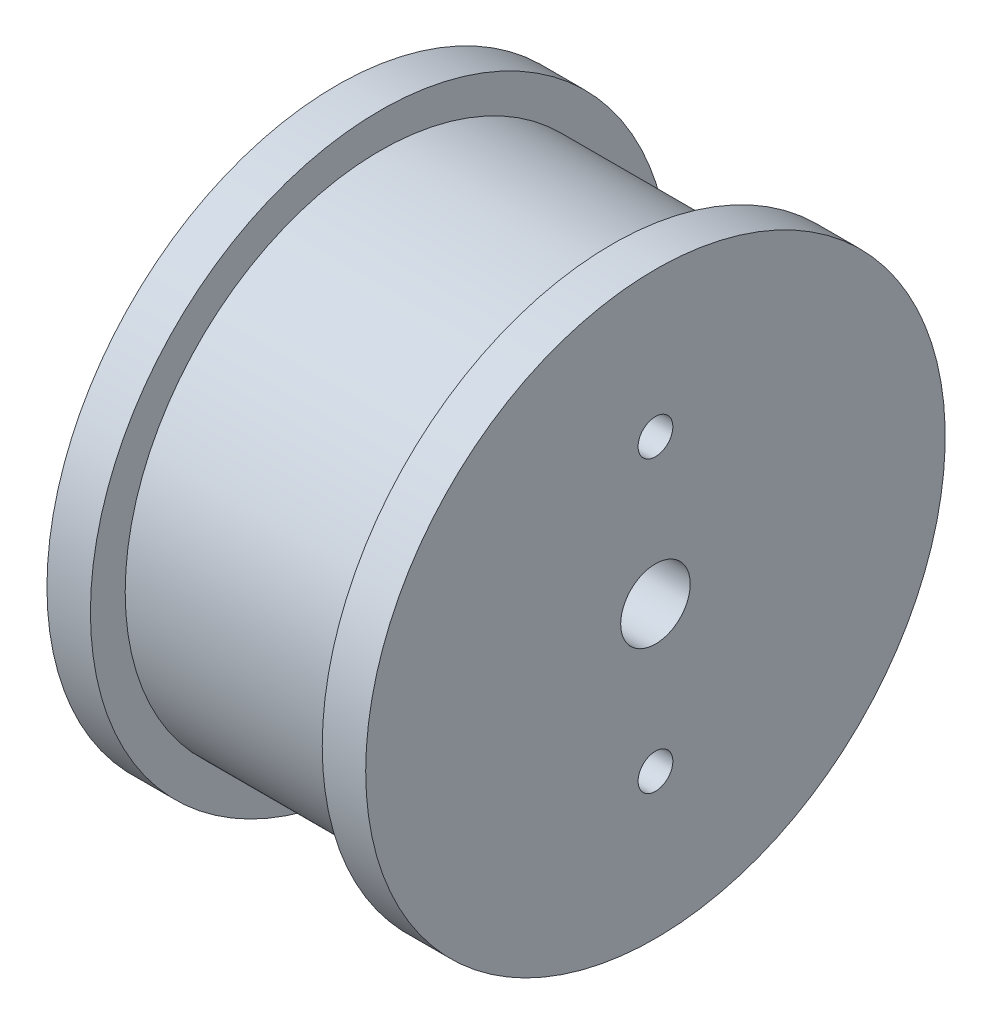
SolidWorks part; units mm, degrees
material "Custom Plastic"
ref_plane "Front Plane" through (0, 0, 0) normal (0, 0, 1) x (1, 0, 0)
ref_plane "Top Plane" through (0, 0, 0) normal (0, 1, 0) x (1, 0, 0)
ref_plane "Right Plane" through (0, 0, 0) normal (1, 0, 0) x (0, 0, -1)
sketch "Sketch1" plane through (0, 0, 0) normal (0, 0, 1) x (1, 0, 0)
  line L0 (0, 75.7198) -> (0, -81.094) construction
  line L1 (-137.2361, 0) -> (119.0019, 0) construction
  line L2 (20, 50) -> (27.5, 50)
  line L3 (27.5, 50) -> (27.5, 6)
  line L4 (27.5, 6) -> (-27.5, 6)
  line L5 (-27.5, 6) -> (-27.5, 50)
  line L6 (-27.5, 50) -> (-20, 50)
  line L7 (-20, 50) -> (-20, 44)
  line L8 (-20, 44) -> (20, 44)
  line L9 (20, 44) -> (20, 50)
  dimension "D1" = 50
  dimension "D2" = 6
  dimension "D3" = 27.5
  dimension "D4" = 90
  dimension "D5" = 7.5
  dimension "D6" = 7.5
  dimension "D7" = 27.5
  dimension "D8" = 40
  dimension "D9" = 6
  dimension "D10" = 50
revolve "Revolve1" add sketch "Sketch1" angle 360 about L1
sketch "Sketch3" plane through (27.5, 0, 0) normal (1, 0, 0) x (0, 0, -1)
  circle A0 centre (0, 25) radius 3
  circle A1 centre (0, -25) radius 3
  dimension "D3" = 6
  dimension "D1" = 25
  dimension "D2" = 50
extrude "Cut-Extrude1" cut sketch "Sketch3" against normal through all
